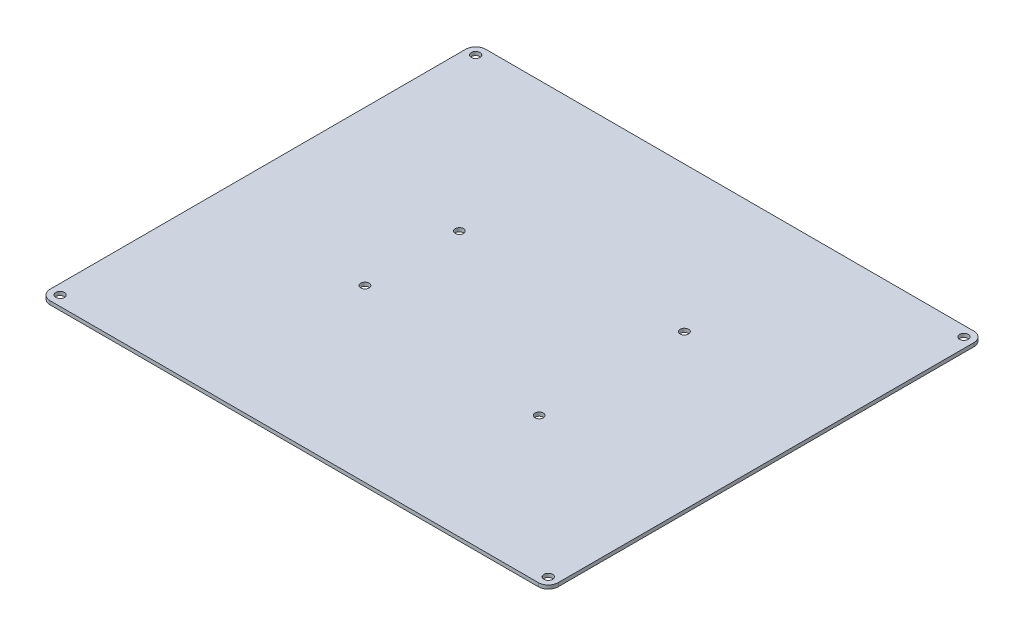
SolidWorks part; units mm, degrees
ref_plane "Front Plane" through (0, 0, 0) normal (0, 0, 1) x (1, 0, 0)
ref_plane "Top Plane" through (0, 0, 0) normal (0, 1, 0) x (1, 0, 0)
ref_plane "Right Plane" through (0, 0, 0) normal (1, 0, 0) x (0, 0, -1)
sketch "Sketch1" plane through (0, 0, 0) normal (0, 1, 0) x (1, 0, 0)
  line L0 (70, 0) -> (70, -120) construction
  line L1 (0, 0) -> (140, 0)
  line L2 (0, 0) -> (0, -120)
  line L3 (0, -120) -> (140, -120)
  line L4 (140, 0) -> (140, -120)
  line L5 (2.75, -2.75) -> (0, -2.75) construction
  line L6 (0, -60) -> (140, -60) construction
  line L7 (42.5, -47) -> (97.5, -40) construction
  line L8 (2.75, 0) -> (2.75, -2.75) construction
  line L10 (97.5, -40) -> (97.5, -80) construction
  line L11 (42.5, -47) -> (42.5, -73) construction
  circle A0 centre (2.75, -2.75) radius 1.2
  circle A1 centre (137.25, -2.75) radius 1.2
  circle A2 centre (137.25, -117.25) radius 1.2
  circle A3 centre (2.75, -117.25) radius 1.2
  circle A4 centre (42.5, -47) radius 1.15
  circle A5 centre (97.5, -40) radius 1.15
  circle A6 centre (42.5, -73) radius 1.15
  circle A7 centre (97.5, -80) radius 1.15
  point P27 (70, -43.5)
  point P28 (97.5, -60)
  point P29 (42.5, -60)
  dimension "D3" = 2.4
  dimension "D4" = 2.75
  dimension "D5" = 2.3
  dimension "D1" = 140
  dimension "D2" = 120
  dimension "D6" = 55
  dimension "D7" = 26
  dimension "D8" = 40
extrude "Boss-Extrude1" add sketch "Sketch1" along normal blind 1
fillet "Fillet1" radius 2.75 4 edges at (0, 0.5, 0) (140, 0.5, 0) (140, 0.5, 120) (0, 0.5, 120)
